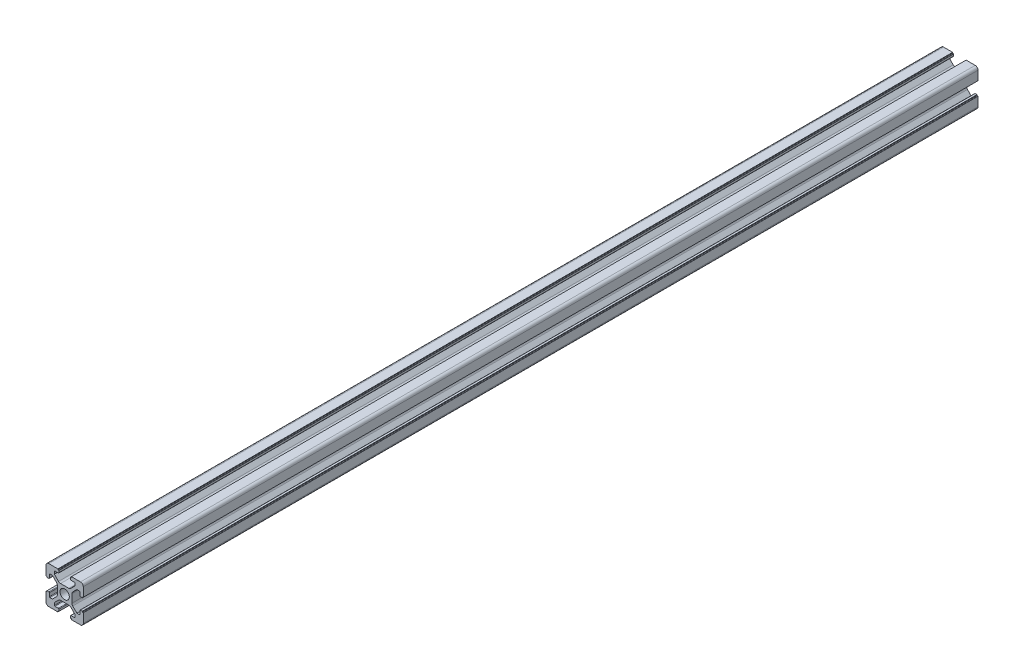
SolidWorks part; units mm, degrees
ref_plane "前视基准面" through (0, 0, 0) normal (0, 0, 1) x (1, 0, 0)
ref_plane "上视基准面" through (0, 0, 0) normal (0, 1, 0) x (1, 0, 0)
ref_plane "右视基准面" through (0, 0, 0) normal (1, 0, 0) x (0, 0, -1)
sketch "草图1" plane through (0, 0, 0) normal (0, 0, 1) x (1, 0, 0)
  line L0 (4.216, 3.2442) -> (6.4367, 5.4649)
  line L1 (6.4367, 5.4649) -> (7.7767, 5.4649)
  line L2 (8.0767, 5.1649) -> (8.0767, 3.3649)
  line L3 (8.3767, 3.0649) -> (9.3767, 3.0649)
  line L4 (9.3767, 3.0649) -> (9.3767, 3.3649)
  line L5 (9.5767, 3.5649) -> (9.8767, 3.5649)
  line L6 (9.8767, 3.5649) -> (9.8767, 8.4649)
  line L7 (8.3767, 9.9649) -> (3.4767, 9.9649)
  line L8 (3.4767, 9.9649) -> (3.4767, 9.6649)
  line L9 (3.2767, 9.4649) -> (2.9767, 9.4649)
  line L10 (2.9767, 9.4649) -> (2.9767, 8.4649)
  line L11 (3.2767, 8.1649) -> (5.0767, 8.1649)
  line L12 (5.3767, 7.8649) -> (5.3767, 6.5249)
  line L13 (5.3767, 6.5249) -> (3.156, 4.3042)
  line L14 (2.0953, 3.8649) -> (-2.342, 3.8649)
  line L15 (-3.4027, 4.3042) -> (-5.6233, 6.5249)
  line L16 (-5.6233, 6.5249) -> (-5.6233, 7.8649)
  line L17 (-5.3233, 8.1649) -> (-3.5233, 8.1649)
  line L18 (-3.2233, 8.4649) -> (-3.2233, 9.4649)
  line L19 (-3.2233, 9.4649) -> (-3.5233, 9.4649)
  line L20 (-3.7233, 9.6649) -> (-3.7233, 9.9649)
  line L21 (-3.7233, 9.9649) -> (-8.6233, 9.9649)
  line L22 (-10.1233, 8.4649) -> (-10.1233, 3.5649)
  line L23 (-10.1233, 3.5649) -> (-9.8233, 3.5649)
  line L24 (-9.6233, 3.3649) -> (-9.6233, 3.0649)
  line L25 (-9.6233, 3.0649) -> (-8.6233, 3.0649)
  line L26 (-8.3233, 3.3649) -> (-8.3233, 5.1649)
  line L27 (-8.0233, 5.4649) -> (-6.6833, 5.4649)
  line L28 (-6.6833, 5.4649) -> (-4.4627, 3.2442)
  line L29 (-4.0233, 2.1836) -> (-4.0233, -2.2538)
  line L30 (-4.4627, -3.3144) -> (-6.6833, -5.5351)
  line L31 (-6.6833, -5.5351) -> (-8.0233, -5.5351)
  line L32 (-8.3233, -5.2351) -> (-8.3233, -3.4351)
  line L33 (-8.6233, -3.1351) -> (-9.6233, -3.1351)
  line L34 (-9.6233, -3.1351) -> (-9.6233, -3.4351)
  line L35 (-9.8233, -3.6351) -> (-10.1233, -3.6351)
  line L36 (-10.1233, -3.6351) -> (-10.1233, -8.5351)
  line L37 (-8.6233, -10.0351) -> (-3.7233, -10.0351)
  line L38 (-3.7233, -10.0351) -> (-3.7233, -9.7351)
  line L39 (-3.5233, -9.5351) -> (-3.2233, -9.5351)
  line L40 (-3.2233, -9.5351) -> (-3.2233, -8.5351)
  line L41 (-3.5233, -8.2351) -> (-5.3233, -8.2351)
  line L42 (-5.6233, -7.9351) -> (-5.6233, -6.5951)
  line L43 (-5.6233, -6.5951) -> (-3.4027, -4.3744)
  line L44 (-2.342, -3.9351) -> (2.0953, -3.9351)
  line L45 (3.156, -4.3744) -> (5.3767, -6.5951)
  line L46 (5.3767, -6.5951) -> (5.3767, -7.9351)
  line L47 (5.0767, -8.2351) -> (3.2767, -8.2351)
  line L48 (2.9767, -8.5351) -> (2.9767, -9.5351)
  line L49 (2.9767, -9.5351) -> (3.2767, -9.5351)
  line L50 (3.4767, -9.7351) -> (3.4767, -10.0351)
  line L51 (3.4767, -10.0351) -> (8.3767, -10.0351)
  line L52 (9.8767, -8.5351) -> (9.8767, -3.6351)
  line L53 (9.8767, -3.6351) -> (9.5767, -3.6351)
  line L54 (9.3767, -3.4351) -> (9.3767, -3.1351)
  line L55 (9.3767, -3.1351) -> (8.3767, -3.1351)
  line L56 (8.0767, -3.4351) -> (8.0767, -5.2351)
  line L57 (7.7767, -5.5351) -> (6.4367, -5.5351)
  line L58 (6.4367, -5.5351) -> (4.216, -3.3144)
  line L59 (3.7767, -2.2538) -> (3.7767, 2.1836)
  circle A0 centre (-0.1233, -0.0351) radius 2.5
  arc A1 (8.0767, 5.1649) -> (7.7767, 5.4649) centre (7.7767, 5.1649) ccw
  arc A2 (8.0767, 3.3649) -> (8.3767, 3.0649) centre (8.3767, 3.3649) ccw
  arc A3 (9.5767, 3.5649) -> (9.3767, 3.3649) centre (9.5767, 3.3649) ccw
  arc A4 (9.8767, 8.4649) -> (8.3767, 9.9649) centre (8.3767, 8.4649) ccw
  arc A5 (3.2767, 9.4649) -> (3.4767, 9.6649) centre (3.2767, 9.6649) ccw
  arc A6 (2.9767, 8.4649) -> (3.2767, 8.1649) centre (3.2767, 8.4649) ccw
  arc A7 (5.3767, 7.8649) -> (5.0767, 8.1649) centre (5.0767, 7.8649) ccw
  arc A8 (2.0953, 3.8649) -> (3.156, 4.3042) centre (2.0953, 5.3649) ccw
  arc A9 (-3.4027, 4.3042) -> (-2.342, 3.8649) centre (-2.342, 5.3649) ccw
  arc A10 (-5.3233, 8.1649) -> (-5.6233, 7.8649) centre (-5.3233, 7.8649) ccw
  arc A11 (-3.5233, 8.1649) -> (-3.2233, 8.4649) centre (-3.5233, 8.4649) ccw
  arc A12 (-3.7233, 9.6649) -> (-3.5233, 9.4649) centre (-3.5233, 9.6649) ccw
  arc A13 (-8.6233, 9.9649) -> (-10.1233, 8.4649) centre (-8.6233, 8.4649) ccw
  arc A14 (-9.6233, 3.3649) -> (-9.8233, 3.5649) centre (-9.8233, 3.3649) ccw
  arc A15 (-8.6233, 3.0649) -> (-8.3233, 3.3649) centre (-8.6233, 3.3649) ccw
  arc A16 (-8.0233, 5.4649) -> (-8.3233, 5.1649) centre (-8.0233, 5.1649) ccw
  arc A17 (-4.0233, 2.1836) -> (-4.4627, 3.2442) centre (-5.5233, 2.1836) ccw
  arc A18 (-4.4627, -3.3144) -> (-4.0233, -2.2538) centre (-5.5233, -2.2538) ccw
  arc A19 (-8.3233, -5.2351) -> (-8.0233, -5.5351) centre (-8.0233, -5.2351) ccw
  arc A20 (-8.3233, -3.4351) -> (-8.6233, -3.1351) centre (-8.6233, -3.4351) ccw
  arc A21 (-9.8233, -3.6351) -> (-9.6233, -3.4351) centre (-9.8233, -3.4351) ccw
  arc A22 (-10.1233, -8.5351) -> (-8.6233, -10.0351) centre (-8.6233, -8.5351) ccw
  arc A23 (-3.5233, -9.5351) -> (-3.7233, -9.7351) centre (-3.5233, -9.7351) ccw
  arc A24 (-3.2233, -8.5351) -> (-3.5233, -8.2351) centre (-3.5233, -8.5351) ccw
  arc A25 (-5.6233, -7.9351) -> (-5.3233, -8.2351) centre (-5.3233, -7.9351) ccw
  arc A26 (-2.342, -3.9351) -> (-3.4027, -4.3744) centre (-2.342, -5.4351) ccw
  arc A27 (3.156, -4.3744) -> (2.0953, -3.9351) centre (2.0953, -5.4351) ccw
  arc A28 (5.0767, -8.2351) -> (5.3767, -7.9351) centre (5.0767, -7.9351) ccw
  arc A29 (3.2767, -8.2351) -> (2.9767, -8.5351) centre (3.2767, -8.5351) ccw
  arc A30 (3.4767, -9.7351) -> (3.2767, -9.5351) centre (3.2767, -9.7351) ccw
  arc A31 (8.3767, -10.0351) -> (9.8767, -8.5351) centre (8.3767, -8.5351) ccw
  arc A32 (9.3767, -3.4351) -> (9.5767, -3.6351) centre (9.5767, -3.4351) ccw
  arc A33 (8.3767, -3.1351) -> (8.0767, -3.4351) centre (8.3767, -3.4351) ccw
  arc A34 (7.7767, -5.5351) -> (8.0767, -5.2351) centre (7.7767, -5.2351) ccw
  arc A35 (3.7767, -2.2538) -> (4.216, -3.3144) centre (5.2767, -2.2538) ccw
  arc A36 (4.216, 3.2442) -> (3.7767, 2.1836) centre (5.2767, 2.1836) ccw
extrude "凸台-拉伸1" add sketch "草图1" along normal blind 480
